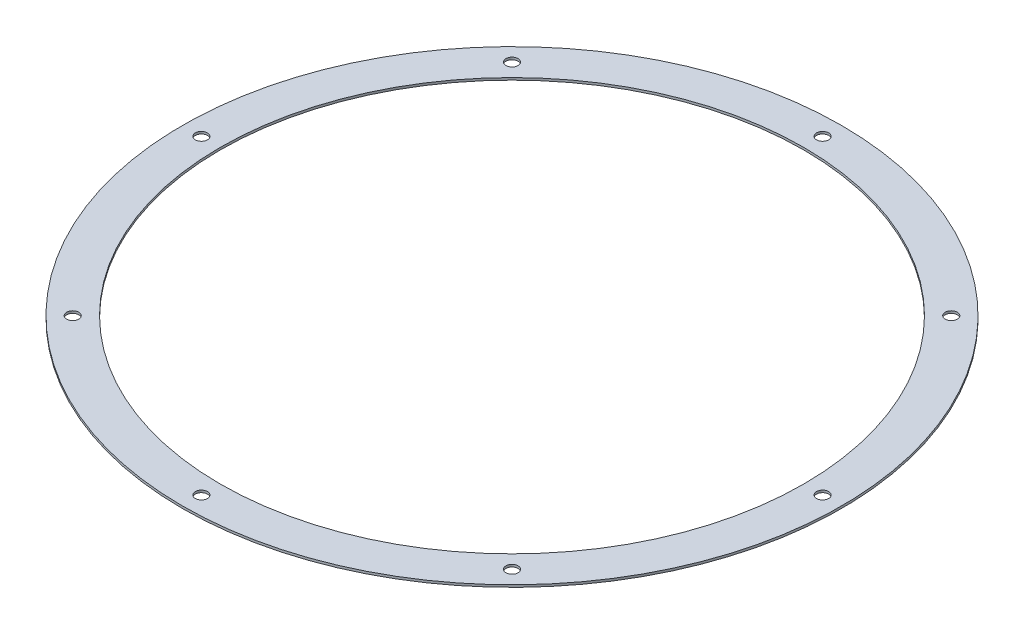
SolidWorks part; units mm, degrees
ref_plane "Front Plane" through (0, 0, 0) normal (0, 0, 1) x (1, 0, 0)
ref_plane "Top Plane" through (0, 0, 0) normal (0, 1, 0) x (1, 0, 0)
ref_plane "Right Plane" through (0, 0, 0) normal (1, 0, 0) x (0, 0, -1)
sketch "Sketch1" plane through (0, 0, 0) normal (0, 1, 0) x (1, 0, 0)
  circle A0 centre (0, 0) radius 385
  circle A1 centre (0, 0) radius 435
  dimension "D1" = 770
  dimension "D2" = 870
extrude "Boss-Extrude1" add sketch "Sketch1" along normal mid plane 3
sketch "Sketch2" plane through (0, 1.5, 0) normal (0, 1, 0) x (1, 0, 0)
  circle A0 centre (0, 0) radius 410 construction
  circle A1 centre (410, 0) radius 8
  circle A7 centre (289.9138, -289.9138) radius 8
  circle A8 centre (0, -410) radius 8
  circle A9 centre (-289.9138, -289.9138) radius 8
  circle A10 centre (-410, 0) radius 8
  circle A11 centre (-289.9138, 289.9138) radius 8
  circle A12 centre (0, 410) radius 8
  circle A13 centre (289.9138, 289.9138) radius 8
  point P5 (285.3999, 294.3584)
  point P8 (0, 0)
  point P18 (0, 0)
  point P23 (0, 0)
  dimension "D1" = 820
  dimension "D2" = 16
  dimension "D3" = 8
extrude "Cut-Extrude1" cut sketch "Sketch2" against normal through all both
